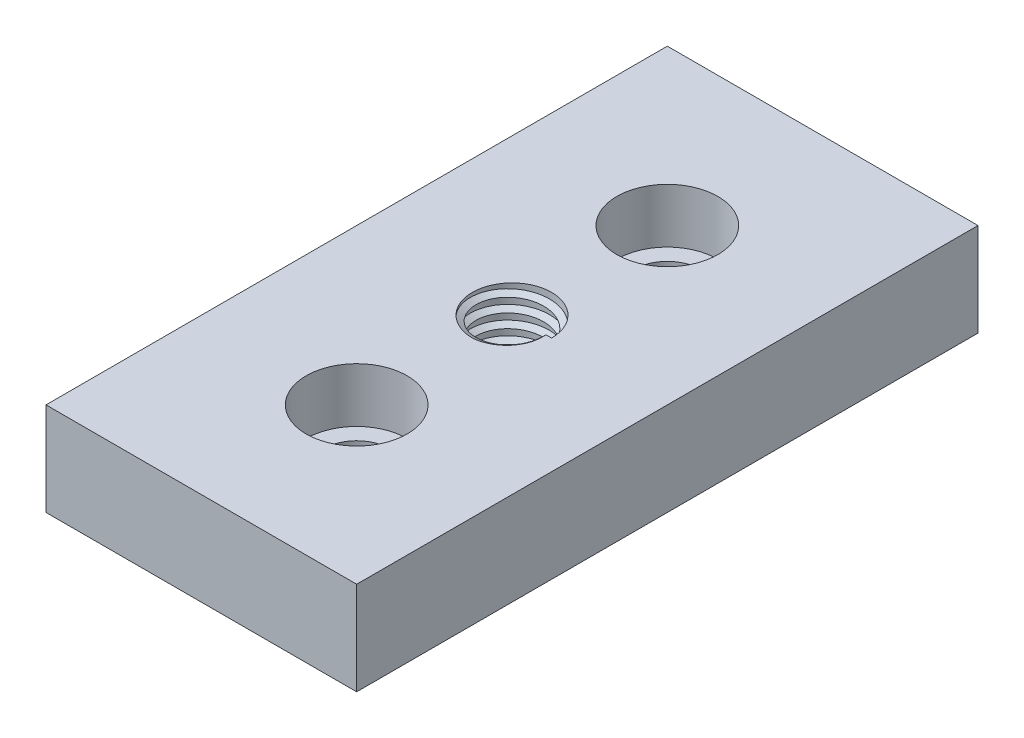
SolidWorks part; units mm, degrees
ref_plane "前视基准面" through (0, 0, 0) normal (0, 0, 1) x (1, 0, 0)
ref_plane "上视基准面" through (0, 0, 0) normal (0, 1, 0) x (1, 0, 0)
ref_plane "右视基准面" through (0, 0, 0) normal (1, 0, 0) x (0, 0, -1)
sketch "草图1" plane through (0, 0, 0) normal (0, 1, 0) x (1, 0, 0)
  line B0 (0, 0) -> (40, 0)
  line B1 (40, 0) -> (40, 80)
  line B2 (40, 80) -> (0, 80)
  line B3 (0, 80) -> (0, 0)
  circle B4 centre (20, 60) radius 4.25
  circle B5 centre (20, 20) radius 4.25
  circle B6 centre (20, 40) radius 5.1
sketch_block_instance "A$C123B28CD-1"
sketch_block "A$C123B28CD"
extrude "凸台-拉伸1" add sketch "草图1" along normal blind 12
sketch "草图3" plane through (0, 12, 0) normal (0, 1, 0) x (1, 0, 0)
  circle A0 centre (20, 20) radius 6.5
  circle A1 centre (20, 60) radius 6.5
extrude "切除-拉伸1" cut sketch "草图3" against normal blind 7
sketch "草图4" plane through (0, 12, 0) normal (0, 1, 0) x (1, 0, 0)
  circle A0 centre (20, 40) radius 5.1
curve "螺旋线/涡状线1" pitch 1.75 height 12 turns 6.8571
ref_plane "基准面2" through (25.1, 12, -40) normal (0, -0.0545, 0.9985) x (1, 0, 0)
sketch "草图5" plane through (25.1, 12, -40) normal (0, -0.0545, 0.9985) x (1, 0, 0)
  line L1 (-0.7404, 0) -> (0.3702, -0.6412)
  line L2 (0.3702, -0.6412) -> (0.3702, 0.6412)
  line L3 (0.3702, 0.6412) -> (-0.7404, 0)
sweep "扫描1" add profiles "草图5" path "螺旋线/涡状线1"
sketch "草图6" plane through (0, 0, -80) normal (0, 0, -1) x (-1, 0, 0)
  line L1 (-40, 12) -> (2.0219, 12)
  line L2 (-40, 12) -> (-40, 14.8458)
  line L3 (-40, 14.8458) -> (2.0219, 14.8458)
  line L4 (2.0219, 12) -> (2.0219, 14.8458)
  line L5 (-40, 0) -> (2.9147, 0)
  line L6 (-40, 0) -> (-40, -10.152)
  line L7 (-40, -10.152) -> (2.9147, -10.152)
  line L8 (2.9147, 0) -> (2.9147, -10.152)
extrude "切除-拉伸2" cut sketch "草图6" against normal through all
